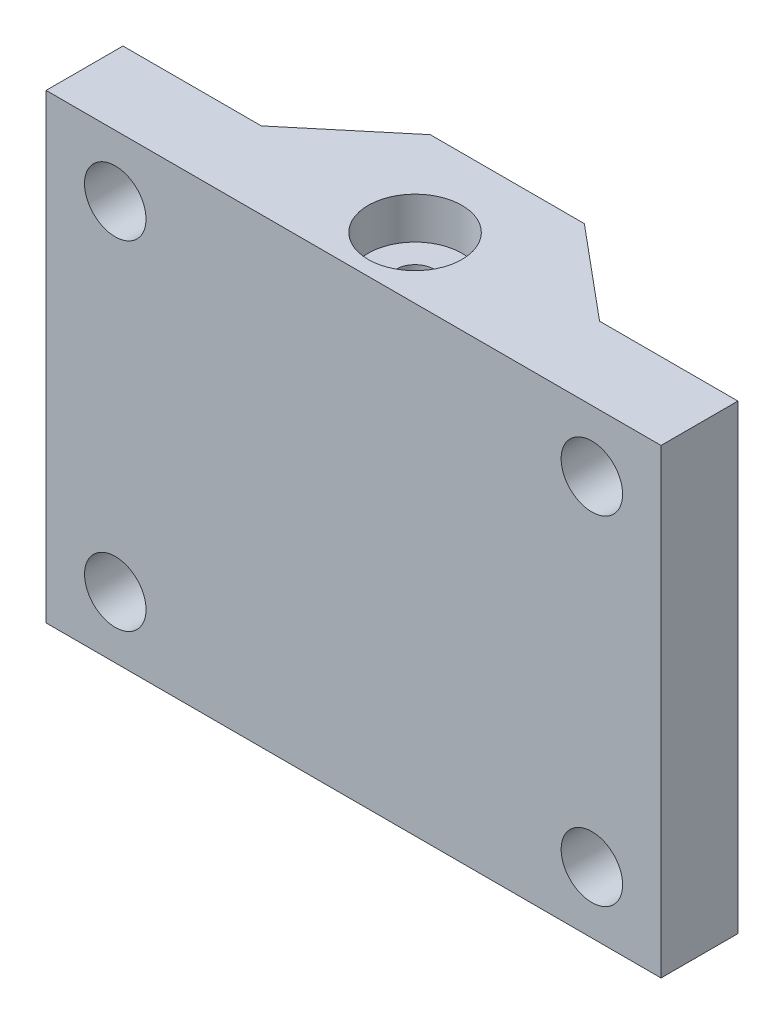
SolidWorks part; units mm, degrees
ref_plane "Front Plane" through (0, 0, 0) normal (0, 0, 1) x (1, 0, 0)
ref_plane "Top Plane" through (0, 0, 0) normal (0, 1, 0) x (1, 0, 0)
ref_plane "Right Plane" through (0, 0, 0) normal (1, 0, 0) x (0, 0, -1)
sketch "Sketch1" plane through (0, 0, 0) normal (0, 1, 0) x (1, 0, 0)
  line L0 (0, 0) -> (-20, 0)
  line L1 (-20, 0) -> (-20, 5)
  line L2 (-20, 5) -> (-11, 5)
  line L6 (11, 5) -> (20, 5)
  line L7 (20, 5) -> (20, 0)
  line L8 (20, 0) -> (0, 0)
  line L9 (0, 0) -> (0, 10) construction
  line L10 (-5.0114, 10) -> (5.0114, 10)
  line L11 (-11, 5) -> (-5.0114, 10)
  line L12 (5.0114, 10) -> (11, 5)
  point P14 (0, 10)
  dimension "D1" = 20
  dimension "D2" = 20
  dimension "D3" = 10
  dimension "D4" = 9
  dimension "D7" = 5
  dimension "D8" = 9
extrude "Boss-Extrude2" add sketch "Sketch1" along normal blind 30
sketch "Sketch2" plane through (0, 30, 0) normal (0, 1, 0) x (1, 0, 0)
  line L0 (0, 0) -> (0, 4) construction
  circle A0 centre (0, 4) radius 1.25
  dimension "D1" = 4
  dimension "D2" = 2.5
extrude "Cut-Extrude1" cut sketch "Sketch2" against normal blind 10
sketch "Sketch4" plane through (0, 0, -5) normal (0, 0, -1) x (-1, 0, 0)
  line L0 (-15.5, 0) -> (20, 0) construction
  line L1 (-20, 0) -> (-11, 0) construction
  line L2 (20, 0) -> (20, 15) construction
  line L3 (20, 30) -> (20, 0) construction
  line L4 (20, 15) -> (-20, 15) construction
  line L5 (-20, 30) -> (-20, 0) construction
  line L6 (-20, 15) -> (-15.5, 30) construction
  line L7 (-20, 30) -> (-11, 30) construction
  line L8 (-15.5, 30) -> (-15.5, 0) construction
  line L9 (0, 0) -> (0, 30) construction
  line L10 (-5.0114, 30) -> (5.0114, 30) construction
  circle A0 centre (-15.5, 4) radius 2
  circle A1 centre (-15.5, 26) radius 2
  circle A2 centre (15.5, 4) radius 2
  circle A3 centre (15.5, 26) radius 2
  dimension "D1" = 4
  dimension "D2" = 4
extrude "Cut-Extrude5" cut sketch "Sketch4" against normal through all
sketch "Sketch5" plane through (0, 30, 0) normal (0, 1, 0) x (1, 0, 0)
  circle A0 centre (0, 4) radius 3.05
  dimension "D1" = 6.1
extrude "Cut-Extrude6" cut sketch "Sketch5" against normal blind 2.7 contours A0
